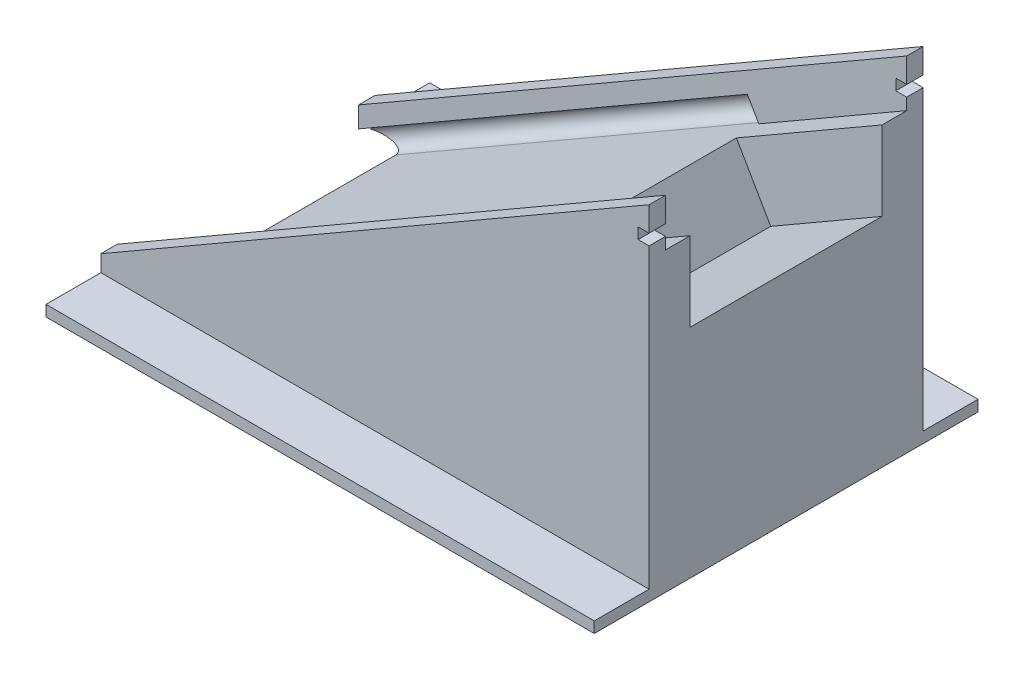
SolidWorks part; units mm, degrees
ref_plane "Front Plane" through (0, 0, 0) normal (0, 0, 1) x (1, 0, 0)
ref_plane "Top Plane" through (0, 0, 0) normal (0, 1, 0) x (1, 0, 0)
ref_plane "Right Plane" through (0, 0, 0) normal (1, 0, 0) x (0, 0, -1)
sketch "Sketch3" plane through (0, 0, 0) normal (0, 1, 0) x (1, 0, 0)
  line L1 (-50, -35) -> (50, -35)
  line L2 (-50, -35) -> (-50, 35)
  line L3 (-50, 35) -> (50, 35)
  line L4 (50, -35) -> (50, 35)
  line L5 (-50, -35) -> (50, 35) construction
  line L6 (-50, 35) -> (50, -35) construction
  point P0 (0, 0)
  dimension "D1" = 100
  dimension "D2" = 70
extrude "Boss-Extrude2" add sketch "Sketch3" along normal blind 2
ref_plane "Plane1" through (0, 0, 0) normal (0, 0, 1) x (1, 0, 0)
sketch "Sketch4" plane through (0, 0, 0) normal (0, 0, 1) x (1, 0, 0)
  line L1 (-50, 2) -> (50, 2) construction
  line L2 (50, 62.735) -> (50, 2)
  line L3 (50, 2) -> (-50, 2)
  line L4 (-50, 2) -> (-50, 5)
  line L5 (-50, 5) -> (50, 62.735)
  dimension "D1" = 30
  dimension "D2" = 3
extrude "Boss-Extrude3" add sketch "Sketch4" along normal mid plane 50
ref_plane "Plane2" through (-35.3349, -20.4006, 0) normal (-0.866, -0.5, 0) x (0, 0, -1)
sketch "Sketch7" plane through (-14.6651, 25.4006, 0) normal (-0.5, 0.866, 0) x (0.866, 0.5, 0)
  line L0 (74.6688, -25) -> (74.6688, 25) construction
  line L1 (74.6688, 17.5) -> (39.6688, 17.5)
  line L2 (74.6688, 17.5) -> (74.6688, -17.5)
  line L3 (74.6688, -17.5) -> (39.6688, -17.5)
  line L4 (39.6688, 17.5) -> (39.6688, -17.5)
  point P6 (39.6688, 0)
  point P7 (74.6688, 0)
  dimension "D1" = 35
  dimension "D2" = 35
extrude "Cut-Extrude3" cut sketch "Sketch7" against normal blind 20
sketch "Sketch5" plane through (-35.3349, -20.4006, 0) normal (-0.866, -0.5, 0) x (0, 0, -1)
  line L8 (-22.5, -21.8495) -> (22.5, -21.8495)
  line L9 (-25, -29.3301) -> (25, -29.3301) construction
  line L10 (-22.5, -26.0495) -> (-22, -26.0495)
  line L11 (-22, -26.0495) -> (-22, -29.3301)
  line L12 (-22, -29.3301) -> (22, -29.3301)
  line L13 (22, -29.3301) -> (22, -26.0495)
  line L14 (22, -26.0495) -> (22.5, -26.0495)
  arc A2 (-22.5, -21.8495) -> (-22.5, -26.0495) centre (-22.5, -23.9495) ccw
  arc A3 (22.5, -26.0495) -> (22.5, -21.8495) centre (22.5, -23.9495) ccw
  point P2 (0, -29.3301)
  point P5 (0, -21.8495)
  dimension "D1" = 4.2
  dimension "D2" = 45
  dimension "D3" = 0.5
extrude "Cut-Extrude1" cut sketch "Sketch5" against normal offset from surface 80 and the other way through all up to plane "Plane2" offset beyond the face yes
sketch "Sketch8" plane through (33.9471, 19.5994, 0) normal (-0.866, -0.5, 0) x (0, 0, 1)
  line L0 (-22.5, 21.8495) -> (22.5, 21.8495) construction
  line L1 (-22, 29.3301) -> (22, 29.3301)
  line L2 (-22, 29.3301) -> (-22, 21.8495)
  line L3 (-22, 21.8495) -> (22, 21.8495)
  line L4 (22, 29.3301) -> (22, 21.8495)
  line L5 (22, 29.3301) -> (22, 26.0495) construction
extrude "Cut-Extrude4" cut sketch "Sketch8" against normal through all
sketch "Sketch9" plane through (50, 0, 0) normal (1, 0, 0) x (0, 0, -1)
  line L0 (-25, 2) -> (-25, 62.735) construction
  line L1 (-25, 56.235) -> (-22, 56.235)
  line L2 (-25, 56.235) -> (-25, 58.235)
  line L3 (-25, 58.235) -> (-22, 58.235)
  line L4 (-22, 56.235) -> (-22, 58.235)
  line L5 (-22, 54.0971) -> (-22, 62.735) construction
  line L6 (0, 34.5043) -> (0, -34.5043) construction
  line L7 (25, 58.235) -> (22, 58.235)
  line L8 (22, 56.235) -> (22, 58.235)
  line L9 (25, 56.235) -> (22, 56.235)
  line L10 (25, 56.235) -> (25, 58.235)
  line L11 (-25, 62.735) -> (-22, 62.735) construction
  dimension "D1" = 2
  dimension "D2" = 4.5
extrude "Cut-Extrude5" cut sketch "Sketch9" against normal blind 2
